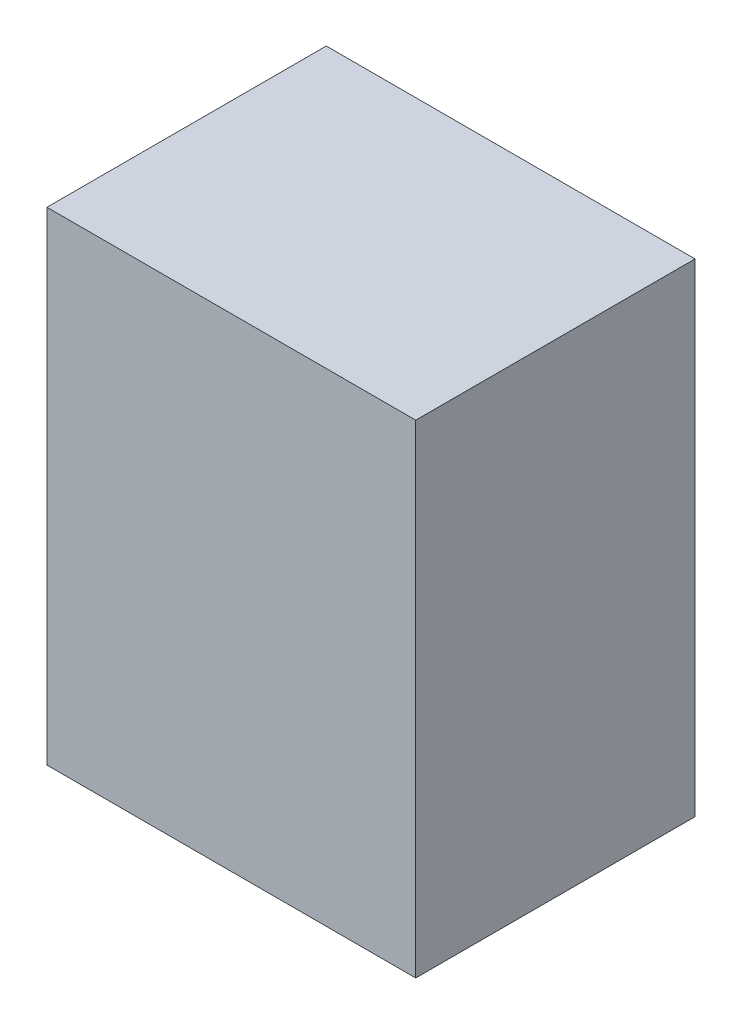
SolidWorks part; units mm, degrees
ref_plane "Front Plane" through (0, 0, 0) normal (0, 0, 1) x (1, 0, 0)
ref_plane "Top Plane" through (0, 0, 0) normal (0, 1, 0) x (1, 0, 0)
ref_plane "Right Plane" through (0, 0, 0) normal (1, 0, 0) x (0, 0, -1)
sketch "Sketch1" plane through (0, 0, 0) normal (0, 0, 1) x (1, 0, 0)
  line L0 (69.2645, -17.43) -> (79.2368, -17.43) construction
  line L1 (69.4645, -17.63) -> (79.0368, -17.63)
  line L2 (69.4645, -17.63) -> (69.4645, -30.17)
  line L3 (69.4645, -30.17) -> (79.0368, -30.17)
  line L4 (79.0368, -17.63) -> (79.0368, -30.17)
  line L5 (79.2368, -30.37) -> (79.2368, -17.43) construction
  line L6 (79.2368, -30.37) -> (69.2645, -30.37) construction
  line L7 (69.2645, -30.37) -> (69.2645, -17.43) construction
  dimension "D1" = 0.2
  dimension "D2" = 0.2
  dimension "D3" = 0.2
  dimension "D4" = 0.2
extrude "Boss-Extrude1" add sketch "Sketch1" along normal blind 7.25
shell "Shell1" thickness 0.5
equation "\"D2@Sketch1\"=\"D1@Sketch1\""
equation "\"D3@Sketch1\"=\"D1@Sketch1\""
equation "\"D4@Sketch1\"=\"D1@Sketch1\""
